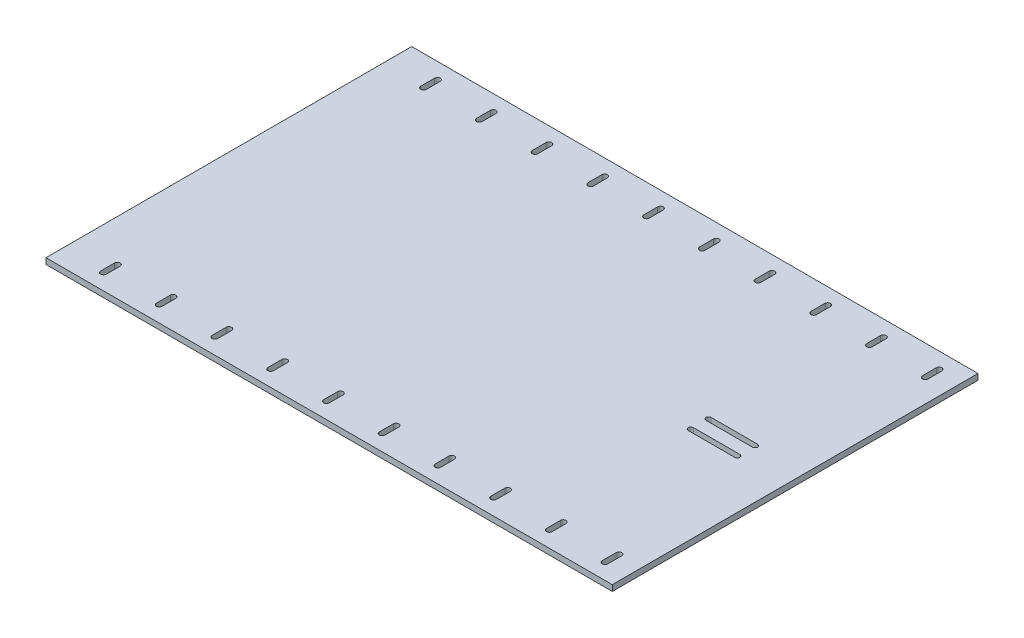
SolidWorks part; units mm, degrees
ref_plane "Front Plane" through (0, 0, 0) normal (0, 0, 1) x (1, 0, 0)
ref_plane "Top Plane" through (0, 0, 0) normal (0, 1, 0) x (1, 0, 0)
ref_plane "Right Plane" through (0, 0, 0) normal (1, 0, 0) x (0, 0, -1)
sketch "Sketch1" plane through (0, 0, 0) normal (0, 1, 0) x (1, 0, 0)
  line L0 (0, 369.15) -> (609.6, 369.15) construction
  line L1 (0, 0) -> (609.6, 0)
  line L2 (0, 0) -> (0, 393.7)
  line L3 (0, 393.7) -> (609.6, 393.7)
  line L4 (609.6, 0) -> (609.6, 393.7)
  line L5 (0, 24.55) -> (609.6, 24.55) construction
  line L6 (584.8, 32.05) -> (584.8, 17.05) construction
  line L9 (587.8, 32.05) -> (587.8, 17.05)
  line L10 (581.8, 32.05) -> (581.8, 17.05)
  line L11 (524.8, 32.05) -> (524.8, 17.05) construction
  line L12 (527.8, 32.05) -> (527.8, 17.05)
  line L13 (521.8, 32.05) -> (521.8, 17.05)
  line L14 (464.8, 32.05) -> (464.8, 17.05) construction
  line L15 (467.8, 32.05) -> (467.8, 17.05)
  line L16 (461.8, 32.05) -> (461.8, 17.05)
  line L17 (404.8, 32.05) -> (404.8, 17.05) construction
  line L18 (407.8, 32.05) -> (407.8, 17.05)
  line L19 (401.8, 32.05) -> (401.8, 17.05)
  line L20 (344.8, 32.05) -> (344.8, 17.05) construction
  line L21 (347.8, 32.05) -> (347.8, 17.05)
  line L22 (341.8, 32.05) -> (341.8, 17.05)
  line L23 (284.8, 32.05) -> (284.8, 17.05) construction
  line L24 (287.8, 32.05) -> (287.8, 17.05)
  line L25 (281.8, 32.05) -> (281.8, 17.05)
  line L26 (224.8, 32.05) -> (224.8, 17.05) construction
  line L27 (227.8, 32.05) -> (227.8, 17.05)
  line L28 (221.8, 32.05) -> (221.8, 17.05)
  line L29 (164.8, 32.05) -> (164.8, 17.05) construction
  line L30 (167.8, 32.05) -> (167.8, 17.05)
  line L31 (161.8, 32.05) -> (161.8, 17.05)
  line L32 (104.8, 32.05) -> (104.8, 17.05) construction
  line L33 (107.8, 32.05) -> (107.8, 17.05)
  line L34 (101.8, 32.05) -> (101.8, 17.05)
  line L35 (44.8, 32.05) -> (44.8, 17.05) construction
  line L36 (47.8, 32.05) -> (47.8, 17.05)
  line L37 (41.8, 32.05) -> (41.8, 17.05)
  line L38 (524.8, 376.65) -> (524.8, 361.65) construction
  line L39 (527.8, 376.65) -> (527.8, 361.65)
  line L40 (521.8, 376.65) -> (521.8, 361.65)
  line L41 (464.8, 376.65) -> (464.8, 361.65) construction
  line L42 (467.8, 376.65) -> (467.8, 361.65)
  line L43 (461.8, 376.65) -> (461.8, 361.65)
  line L44 (404.8, 376.65) -> (404.8, 361.65) construction
  line L45 (407.8, 376.65) -> (407.8, 361.65)
  line L46 (401.8, 376.65) -> (401.8, 361.65)
  line L47 (344.8, 376.65) -> (344.8, 361.65) construction
  line L48 (347.8, 376.65) -> (347.8, 361.65)
  line L49 (341.8, 376.65) -> (341.8, 361.65)
  line L50 (284.8, 376.65) -> (284.8, 361.65) construction
  line L51 (287.8, 376.65) -> (287.8, 361.65)
  line L52 (281.8, 376.65) -> (281.8, 361.65)
  line L53 (224.8, 376.65) -> (224.8, 361.65) construction
  line L54 (227.8, 376.65) -> (227.8, 361.65)
  line L55 (221.8, 376.65) -> (221.8, 361.65)
  line L56 (164.8, 376.65) -> (164.8, 361.65) construction
  line L57 (167.8, 376.65) -> (167.8, 361.65)
  line L58 (161.8, 376.65) -> (161.8, 361.65)
  line L59 (104.8, 376.65) -> (104.8, 361.65) construction
  line L60 (107.8, 376.65) -> (107.8, 361.65)
  line L61 (101.8, 376.65) -> (101.8, 361.65)
  line L62 (44.8, 376.65) -> (44.8, 361.65) construction
  line L63 (47.8, 376.65) -> (47.8, 361.65)
  line L64 (41.8, 376.65) -> (41.8, 361.65)
  line L65 (584.8, 376.65) -> (584.8, 361.65) construction
  line L66 (587.8, 376.65) -> (587.8, 361.65)
  line L67 (581.8, 376.65) -> (581.8, 361.65)
  line L68 (609.6, 187.325) -> (0, 187.325) construction
  line L69 (0, 206.375) -> (609.6, 206.375) construction
  line L70 (506.85, 206.375) -> (556.85, 206.375) construction
  line L71 (506.85, 209.125) -> (556.85, 209.125)
  line L72 (506.85, 203.625) -> (556.85, 203.625)
  line L73 (506.85, 187.325) -> (556.85, 187.325) construction
  line L74 (506.85, 190.075) -> (556.85, 190.075)
  line L75 (506.85, 184.575) -> (556.85, 184.575)
  arc A22 (587.8, 32.05) -> (581.8, 32.05) centre (584.8, 32.05) ccw
  arc A23 (581.8, 17.05) -> (587.8, 17.05) centre (584.8, 17.05) ccw
  arc A24 (506.85, 209.125) -> (506.85, 203.625) centre (506.85, 206.375) ccw
  arc A25 (527.8, 32.05) -> (521.8, 32.05) centre (524.8, 32.05) ccw
  arc A26 (521.8, 17.05) -> (527.8, 17.05) centre (524.8, 17.05) ccw
  arc A27 (467.8, 32.05) -> (461.8, 32.05) centre (464.8, 32.05) ccw
  arc A28 (461.8, 17.05) -> (467.8, 17.05) centre (464.8, 17.05) ccw
  arc A29 (407.8, 32.05) -> (401.8, 32.05) centre (404.8, 32.05) ccw
  arc A30 (401.8, 17.05) -> (407.8, 17.05) centre (404.8, 17.05) ccw
  arc A31 (347.8, 32.05) -> (341.8, 32.05) centre (344.8, 32.05) ccw
  arc A32 (341.8, 17.05) -> (347.8, 17.05) centre (344.8, 17.05) ccw
  arc A33 (287.8, 32.05) -> (281.8, 32.05) centre (284.8, 32.05) ccw
  arc A34 (281.8, 17.05) -> (287.8, 17.05) centre (284.8, 17.05) ccw
  arc A35 (227.8, 32.05) -> (221.8, 32.05) centre (224.8, 32.05) ccw
  arc A36 (221.8, 17.05) -> (227.8, 17.05) centre (224.8, 17.05) ccw
  arc A37 (167.8, 32.05) -> (161.8, 32.05) centre (164.8, 32.05) ccw
  arc A38 (161.8, 17.05) -> (167.8, 17.05) centre (164.8, 17.05) ccw
  arc A39 (107.8, 32.05) -> (101.8, 32.05) centre (104.8, 32.05) ccw
  arc A40 (101.8, 17.05) -> (107.8, 17.05) centre (104.8, 17.05) ccw
  arc A41 (47.8, 32.05) -> (41.8, 32.05) centre (44.8, 32.05) ccw
  arc A42 (41.8, 17.05) -> (47.8, 17.05) centre (44.8, 17.05) ccw
  arc A43 (527.8, 376.65) -> (521.8, 376.65) centre (524.8, 376.65) ccw
  arc A44 (521.8, 361.65) -> (527.8, 361.65) centre (524.8, 361.65) ccw
  arc A45 (467.8, 376.65) -> (461.8, 376.65) centre (464.8, 376.65) ccw
  arc A46 (461.8, 361.65) -> (467.8, 361.65) centre (464.8, 361.65) ccw
  arc A47 (407.8, 376.65) -> (401.8, 376.65) centre (404.8, 376.65) ccw
  arc A48 (401.8, 361.65) -> (407.8, 361.65) centre (404.8, 361.65) ccw
  arc A49 (347.8, 376.65) -> (341.8, 376.65) centre (344.8, 376.65) ccw
  arc A50 (341.8, 361.65) -> (347.8, 361.65) centre (344.8, 361.65) ccw
  arc A51 (287.8, 376.65) -> (281.8, 376.65) centre (284.8, 376.65) ccw
  arc A52 (281.8, 361.65) -> (287.8, 361.65) centre (284.8, 361.65) ccw
  arc A53 (227.8, 376.65) -> (221.8, 376.65) centre (224.8, 376.65) ccw
  arc A54 (221.8, 361.65) -> (227.8, 361.65) centre (224.8, 361.65) ccw
  arc A55 (167.8, 376.65) -> (161.8, 376.65) centre (164.8, 376.65) ccw
  arc A56 (161.8, 361.65) -> (167.8, 361.65) centre (164.8, 361.65) ccw
  arc A57 (107.8, 376.65) -> (101.8, 376.65) centre (104.8, 376.65) ccw
  arc A58 (101.8, 361.65) -> (107.8, 361.65) centre (104.8, 361.65) ccw
  arc A59 (47.8, 376.65) -> (41.8, 376.65) centre (44.8, 376.65) ccw
  arc A60 (41.8, 361.65) -> (47.8, 361.65) centre (44.8, 361.65) ccw
  arc A61 (587.8, 376.65) -> (581.8, 376.65) centre (584.8, 376.65) ccw
  arc A62 (581.8, 361.65) -> (587.8, 361.65) centre (584.8, 361.65) ccw
  arc A63 (556.85, 203.625) -> (556.85, 209.125) centre (556.85, 206.375) ccw
  arc A64 (506.85, 190.075) -> (506.85, 184.575) centre (506.85, 187.325) ccw
  arc A65 (556.85, 184.575) -> (556.85, 190.075) centre (556.85, 187.325) ccw
  point P12 (524.8, 24.55)
  point P19 (464.8, 24.55)
  point P26 (404.8, 24.55)
  point P32 (531.85, 206.375)
  point P38 (531.85, 187.325)
  point P44 (0, 0)
  point P51 (584.8, 24.55)
  point P63 (344.8, 24.55)
  point P70 (284.8, 24.55)
  point P77 (224.8, 24.55)
  point P84 (164.8, 24.55)
  point P91 (104.8, 24.55)
  point P98 (44.8, 24.55)
  point P105 (524.8, 369.15)
  point P112 (464.8, 369.15)
  point P119 (404.8, 369.15)
  point P126 (344.8, 369.15)
  point P133 (284.8, 369.15)
  point P140 (224.8, 369.15)
  point P147 (164.8, 369.15)
  point P154 (104.8, 369.15)
  point P161 (44.8, 369.15)
  point P168 (584.8, 369.15)
  dimension "D5" = 60
  dimension "D12" = 15
  dimension "D15" = 50
  dimension "D1" = 393.7
  dimension "D2" = 609.6
  dimension "D3" = 10
  dimension "D4" = 2
  dimension "D8" = 187.325
  dimension "D9" = 5.5
  dimension "D10" = 24.55
  dimension "D11" = 24.55
  dimension "D13" = 6
  dimension "D14" = 24.8
  dimension "D6" = 344.6
  dimension "D7" = 187.325
  dimension "D16" = 50
extrude "Boss-Extrude1" add sketch "Sketch1" along normal blind 6.35
